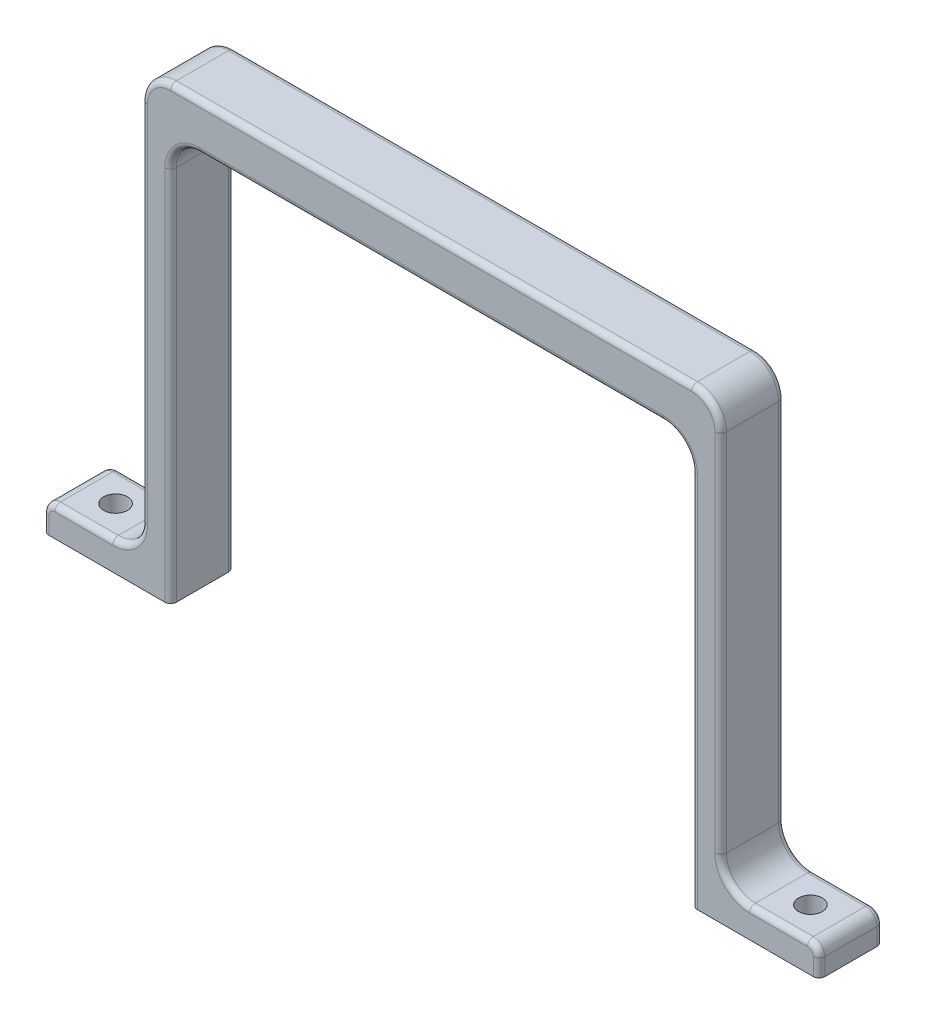
SolidWorks part; units mm, degrees
ref_plane "Plan de face" through (0, 0, 0) normal (0, 0, 1) x (1, 0, 0)
ref_plane "Plan de dessus" through (0, 0, 0) normal (0, 1, 0) x (1, 0, 0)
ref_plane "Plan de droite" through (0, 0, 0) normal (1, 0, 0) x (0, 0, -1)
sketch "Esquisse1" plane through (0, 0, 0) normal (0, 0, 1) x (1, 0, 0)
  line L0 (0, 0) -> (109.8698, 0) construction
  line L1 (0, 0) -> (-101.741, 0) construction
  line L2 (-67, 0) -> (-45, 0)
  line L3 (-45, 0) -> (-45, 65)
  line L4 (0, 0) -> (0, 104.0446) construction
  line L5 (-40, 70) -> (40, 70)
  line L7 (45, 78) -> (-45, 78)
  line L8 (-50, 73) -> (-50, 10)
  line L9 (-55, 5) -> (-65, 5)
  line L10 (-67, 3) -> (-67, 0)
  line L11 (67, 0) -> (45, 0)
  line L12 (67, 3) -> (67, 0)
  line L13 (55, 5) -> (65, 5)
  line L14 (50, 73) -> (50, 10)
  line L15 (45, 0) -> (45, 65)
  arc A0 (-50, 10) -> (-55, 5) centre (-55, 10) cw
  arc A1 (-65, 5) -> (-67, 3) centre (-65, 3) ccw
  arc A2 (-45, 78) -> (-50, 73) centre (-45, 73) ccw
  arc A3 (-45, 65) -> (-40, 70) centre (-40, 65) cw
  arc A4 (45, 65) -> (40, 70) centre (40, 65) ccw
  arc A5 (45, 78) -> (50, 73) centre (45, 73) cw
  arc A6 (65, 5) -> (67, 3) centre (65, 3) cw
  arc A7 (50, 10) -> (55, 5) centre (55, 10) ccw
  point P6 (0, 70)
  point P9 (45, 70)
  point P15 (-50, 5)
  point P18 (-67, 5)
  point P23 (-45, 70)
  point P39 (0, 78)
  point P40 (67, 5)
  point P41 (50, 5)
  dimension "D7" = 5
  dimension "D8" = 2
  dimension "D10" = 5
  dimension "D11" = 5
  dimension "D1" = 78
  dimension "D2" = 5
  dimension "D3" = 45
  dimension "D4" = 8
  dimension "D5" = 10
  dimension "D6" = 5
extrude "Boss.-Extru.1" add sketch "Esquisse1" along normal blind 11
fillet "Congé1" radius 1 36 edges at (45, 32.5, 11) (43.5355, 68.5355, 11) (0, 70, 11) (-43.5355, 68.5355, 11) (-45, 32.5, 0) (-43.5355, 68.5355, 0) (45, 32.5, 0) (43.5355, 68.5355, 0) (67, 1.5, 0) (66.4142, 4.4142, 0) (60, 5, 0) (51.4645, 6.4645, 0) (50, 41.5, 0) (48.5355, 76.5355, 0) (0, 78, 0) (-48.5355, 76.5355, 0) (-67, 1.5, 0) (-66.4142, 4.4142, 0) (-60, 5, 0) (-51.4645, 6.4645, 0) (67, 1.5, 11) (66.4142, 4.4142, 11) (60, 5, 11) (51.4645, 6.4645, 11) (50, 41.5, 11) (48.5355, 76.5355, 11) (-67, 1.5, 11) (-66.4142, 4.4142, 11) (-60, 5, 11) (-51.4645, 6.4645, 11) (-50, 41.5, 11) (-48.5355, 76.5355, 11) (-45, 32.5, 11) (0, 70, 0) (-50, 41.5, 0) (0, 78, 11)
sketch "Esquisse2" plane through (0, 70, 0) normal (0, -1, 0) x (1, 0, 0)
  line L0 (0, 0) -> (0, 30.7322) construction
  line L1 (-40, 5.5) -> (40, 5.5) construction
  line L5 (40, 1) -> (40, 10)
  line L6 (40, 10) -> (-40, 10)
  line L7 (-40, 10) -> (-40, 1)
  line L8 (-40, 1) -> (40, 1)
  line L9 (40, 1) -> (40, 10)
  line L10 (40, 10) -> (-40, 10)
  line L11 (-40, 10) -> (-40, 1)
  line L12 (-40, 1) -> (40, 1)
  circle A0 centre (-33.5, 5.5) radius 3.2
  circle A1 centre (33.5, 5.5) radius 3.2
  dimension "D3" = 6.4
  dimension "D2" = 67
  dimension "D1" = 0
extrude "Enlèv. mat.-Extru.1" cut sketch "Esquisse2" against normal blind 5 contours A0 | A1
sketch "Esquisse3" plane through (0, 5, 0) normal (0, 1, 0) x (1, 0, 0)
  line L0 (0, 0) -> (0, -46.122) construction
  line L1 (-55, -5.5) -> (-65, -5.5) construction
  line L2 (-60, -1) -> (-60, -10) construction
  line L5 (-55, -10) -> (-55, -1)
  line L6 (-55, -1) -> (-65, -1)
  line L7 (-65, -1) -> (-65, -10)
  line L8 (-65, -10) -> (-55, -10)
  line L9 (-55, -10) -> (-55, -1)
  line L10 (-55, -1) -> (-65, -1)
  line L11 (-65, -1) -> (-65, -10)
  line L12 (-65, -10) -> (-55, -10)
  circle A0 centre (-60, -5.5) radius 2.05
  circle A1 centre (60, -5.5) radius 2.05
  dimension "D2" = 4.1
  dimension "D3" = 120
  dimension "D1" = 0
extrude "Enlèv. mat.-Extru.2" cut sketch "Esquisse3" against normal through all contours A0 | A1
